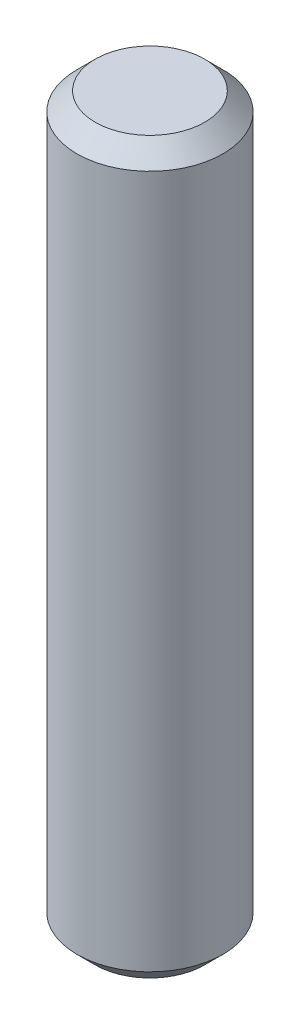
SolidWorks part; units mm, degrees
material "AISI 1020"
ref_plane "Спереди" through (0, 0, 0) normal (0, 0, 1) x (1, 0, 0)
ref_plane "Сверху" through (0, 0, 0) normal (0, 1, 0) x (1, 0, 0)
ref_plane "Справа" through (0, 0, 0) normal (1, 0, 0) x (0, 0, -1)
sketch "Эскиз1" plane through (0, 0, 0) normal (0, 1, 0) x (1, 0, 0)
  circle A0 centre (0, 0) radius 4
  dimension "D1" = 8
extrude "Бобышка-Вытянуть1" add sketch "Эскиз1" along normal blind 40
chamfer "Фаска1" distance 1 angle 45 2 edges at (0, 0, 4) (0, 40, 4)
